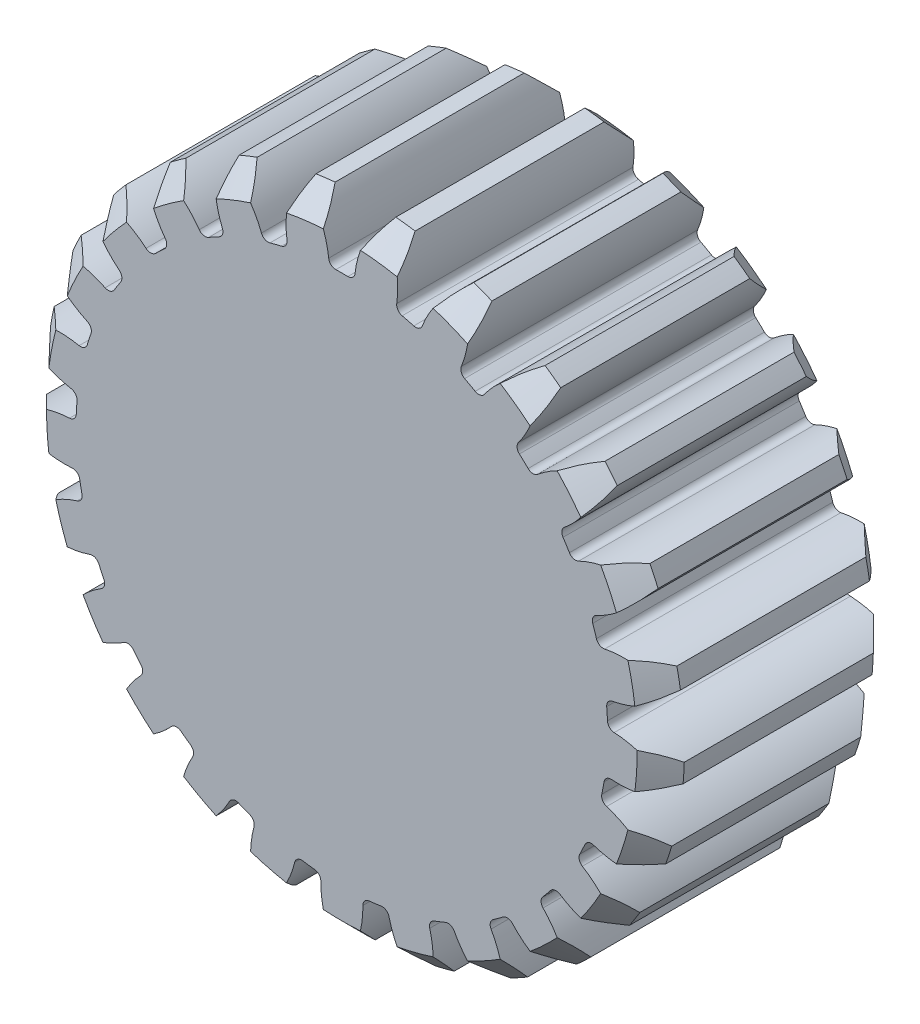
SolidWorks part; units mm, degrees
material "Plain Carbon Steel"
ref_plane "Front Plane" through (0, 0, 0) normal (0, 0, 1) x (1, 0, 0)
ref_plane "Top Plane" through (0, 0, 0) normal (0, 1, 0) x (1, 0, 0)
ref_plane "Right Plane" through (0, 0, 0) normal (1, 0, 0) x (0, 0, -1)
sketch "Sketch2" plane through (0, 0, 0) normal (0, 0, 1) x (1, 0, 0)
  circle A0 centre (0, 0) radius 25
  circle A1 centre (0, 0) radius 27
  circle A2 centre (0, 0) radius 22.5
  dimension "D1" = 50
  dimension "D2" = 54
  dimension "D3" = 4.5
extrude "Boss-Extrude1" add sketch "Sketch2" along normal mid plane 20 contours A1
sketch "Sketch3" plane through (0, 0, 0) normal (0, 0, 1) x (1, 0, 0)
  line L0 (0, 0) -> (0, 27) construction
  line L1 (-1.5698, 24.9507) -> (1.5698, 24.9507) construction
  line L2 (-1.072, 22.4744) -> (0, 0) construction
  line L3 (0, 20.6378) -> (-2.6344, 27.8758) construction
  line L4 (0, 0) -> (3.384, 26.7871) construction
  line L5 (1.5698, 24.9507) -> (4.6845, 24.5572) construction
  circle A0 centre (0, 0) radius 27 construction
  arc A1 (-3.3153, 27.803) -> (-1.072, 22.4744) centre (-9.4743, 22.0737) cw
  arc A2 (3.3153, 27.803) -> (1.072, 22.4744) centre (9.4743, 22.0737) ccw
  circle A3 centre (0, 0) radius 22.5 construction
  arc A4 (1.072, 22.4744) -> (-1.072, 22.4744) centre (0, 0) ccw
  circle A6 centre (0, 0) radius 25 construction
  circle A7 centre (0, 0) radius 28
  arc A8 (3.3153, 27.803) -> (-3.3153, 27.803) centre (0, 0) ccw
  circle A9 centre (0, 0) radius 27 construction
  dimension "D2" = 20
  dimension "D3" = 7.2
  dimension "D1" = 1
extrude "Cut-Extrude1" cut sketch "Sketch3" against normal through all both and the other way through all
fillet "Fillet1" radius 0.6 2 edges at (1.072, 22.4744, 0) (-1.072, 22.4744, 0)
chamfer "Chamfer1" distance 2 2 edges at (0, -27, -10) (0, -27, 10)
pattern_circular "CirPattern1" count 25 over 360 about axis through (0, 0, 0) along (0, 0, 1) of "Fillet1", "Cut-Extrude1"
equation "\"Module\"= 2mm"
equation "\"Number of Teeth\"= 25"
equation "\"D1@Sketch2\"=\"Module\" * \"Number of Teeth\""
equation "\"D2@Sketch2\"=(\"Number of Teeth\" + 2) * \"Module\""
equation "\"D3@Sketch2\"=\"Module\" * if( \"Module\" => 1.25, 2.25, 2.4) "
equation "\"D3@Sketch3\"=180deg / \"Number of Teeth\""
equation "\"D1@Fillet1\"=0.3 * \"Module\""
equation "\"D1@CirPattern1\"=\"Number of Teeth\""
equation "\"D1@Chamfer1\"=\"Module\""
equation "\"Pressure Angle\"= 20deg"
equation "\"D2@Sketch3\"=\"Pressure Angle\""
